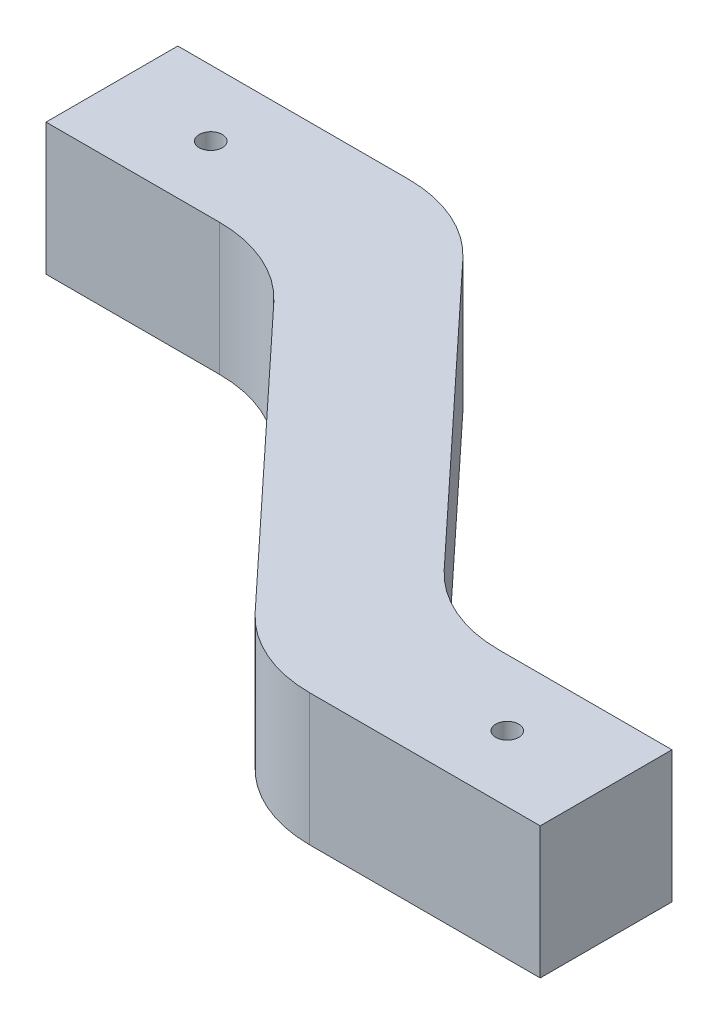
SolidWorks part; units mm, degrees
ref_plane "Alzado" through (0, 0, 0) normal (0, 0, 1) x (1, 0, 0)
ref_plane "Planta" through (0, 0, 0) normal (0, 1, 0) x (1, 0, 0)
ref_plane "Vista lateral" through (0, 0, 0) normal (1, 0, 0) x (0, 0, -1)
sketch "Croquis1" plane through (0, 0, 0) normal (0, 1, 0) x (1, 0, 0)
  line L0 (-65, 0) -> (65, 0) construction
  line L1 (-65, 0) -> (-21.3058, 0)
  line L2 (-21.3058, 0) -> (30, -55)
  line L3 (30, -55) -> (65, -55)
  line L4 (65, -55) -> (65, -75)
  line L5 (65, -75) -> (21.3058, -75)
  line L6 (21.3058, -75) -> (-30, -20)
  line L7 (-30, -20) -> (-65, -20)
  line L8 (-65, -20) -> (-65, 0)
  line L9 (-65, -10) -> (-50, -10) construction
  line L10 (50, -65) -> (65, -65) construction
  circle A0 centre (-50, -10) radius 1.75
  circle A1 centre (50, -65) radius 1.75
  point P0 (-65, -10)
  point P4 (0, 0)
  point P13 (65, -65)
  dimension "D8" = 3.5
  dimension "D1" = 130
  dimension "D2" = 20
  dimension "D3" = 35
  dimension "D4" = 55
  dimension "D5" = 20
  dimension "D6" = 15
  dimension "D7" = 15
extrude "Saliente-Extruir1" add sketch "Croquis1" along normal blind 20
fillet "Redondeo1" radius 20 4 edges at (21.3058, 10, 75) (30, 10, 55) (-21.3058, 10, 0) (-30, 10, 20)
sketch "Croquis3" plane through (0, 20, 0) normal (0, 1, 0) x (1, 0, 0)
  line L5 (65, -52.5479) -> (45, -52.5479)
  line L6 (45, -52.5479) -> (45, -75)
  line L7 (45, -75) -> (65, -75)
  line L8 (65, -75) -> (65, -52.5479)
  line L9 (30, -75) -> (65, -75) construction
  dimension "D2" = 20
extrude "Cortar-Extruir2" [suppressed] cut sketch "Croquis3" against normal blind 10
sketch "Croquis5" plane through (0, 0, 0) normal (0, -1, 0) x (1, 0, 0)
  line L0 (-65, 0) -> (-45, 0)
  line L1 (-45, 0) -> (-45, 24.0911)
  line L2 (-45, 24.0911) -> (-65, 24.0911)
  line L3 (-65, 24.0911) -> (-65, 0)
  dimension "D1" = 20
extrude "Cortar-Extruir3" [suppressed] cut sketch "Croquis5" against normal blind 10
